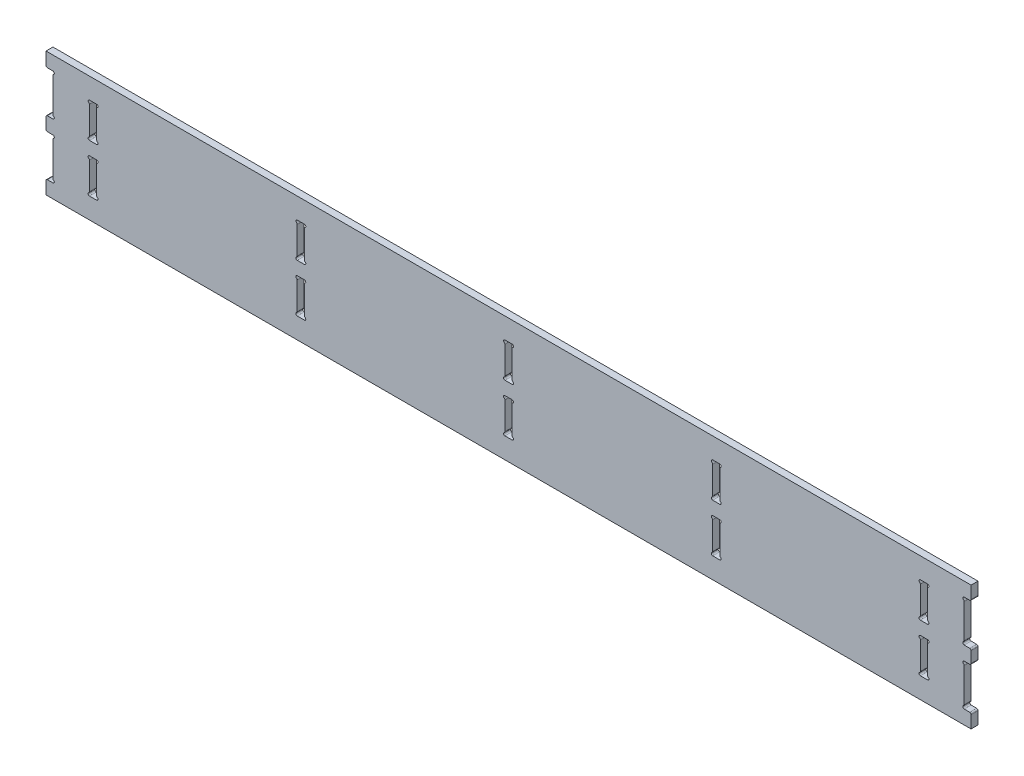
SolidWorks part; units mm, degrees
material "Plain Carbon Steel"
ref_plane "Front Plane" through (0, 0, 0) normal (0, 0, 1) x (1, 0, 0)
ref_plane "Top Plane" through (0, 0, 0) normal (0, 1, 0) x (1, 0, 0)
ref_plane "Right Plane" through (0, 0, 0) normal (1, 0, 0) x (0, 0, -1)
sketch "Sketch2" plane through (0, 0, 0) normal (0, 0, 1) x (1, 0, 0)
  line L0 (55, 0) -> (-55, 0) construction
  line L1 (-334, 90) -> (334, 90)
  line L2 (-334, 90) -> (-334, 0)
  line L3 (-334, 0) -> (334, 0)
  line L4 (334, 90) -> (334, 0)
  point P6 (0, 0)
  dimension "D1" = 668
  dimension "D2" = 90
extrude "Boss-Extrude1" add sketch "Sketch2" along normal blind 5
sketch "Sketch4" plane through (0, 0, 0) normal (0, 0, -1) x (-1, 0, 0)
  line L0 (0, 2.75) -> (0, -2.75) construction
  line L1 (-2.6, 75) -> (2.6, 75)
  line L2 (-2.6, 75) -> (-2.6, 49.8)
  line L3 (-2.6, 49.8) -> (2.6, 49.8)
  line L4 (2.6, 75) -> (2.6, 49.8)
  line L5 (-2.6, 40.2) -> (2.6, 40.2)
  line L6 (-2.6, 40.2) -> (-2.6, 15)
  line L7 (-2.6, 15) -> (2.6, 15)
  line L8 (2.6, 40.2) -> (2.6, 15)
  line L9 (-334, 90) -> (334, 90) construction
  line L10 (2.75, 0) -> (-2.75, 0) construction
  line L11 (147.4, 75) -> (152.6, 75)
  line L12 (147.4, 75) -> (147.4, 49.8)
  line L13 (147.4, 49.8) -> (152.6, 49.8)
  line L14 (152.6, 75) -> (152.6, 49.8)
  line L15 (147.4, 40.2) -> (152.6, 40.2)
  line L16 (147.4, 40.2) -> (147.4, 15)
  line L17 (147.4, 15) -> (152.6, 15)
  line L18 (152.6, 40.2) -> (152.6, 15)
  line L19 (297.4, 75) -> (302.6, 75)
  line L20 (297.4, 75) -> (297.4, 49.8)
  line L21 (297.4, 49.8) -> (302.6, 49.8)
  line L22 (302.6, 75) -> (302.6, 49.8)
  line L23 (297.4, 40.2) -> (302.6, 40.2)
  line L24 (297.4, 40.2) -> (297.4, 15)
  line L25 (297.4, 15) -> (302.6, 15)
  line L26 (302.6, 40.2) -> (302.6, 15)
  line L27 (-302.6, 40.2) -> (-302.6, 15)
  line L28 (-297.4, 15) -> (-302.6, 15)
  line L29 (-297.4, 40.2) -> (-297.4, 15)
  line L30 (-297.4, 40.2) -> (-302.6, 40.2)
  line L31 (-302.6, 75) -> (-302.6, 49.8)
  line L32 (-297.4, 49.8) -> (-302.6, 49.8)
  line L33 (-297.4, 75) -> (-297.4, 49.8)
  line L34 (-297.4, 75) -> (-302.6, 75)
  line L35 (-152.6, 40.2) -> (-152.6, 15)
  line L36 (-147.4, 15) -> (-152.6, 15)
  line L37 (-147.4, 40.2) -> (-147.4, 15)
  line L38 (-147.4, 40.2) -> (-152.6, 40.2)
  line L39 (-152.6, 75) -> (-152.6, 49.8)
  line L40 (-147.4, 49.8) -> (-152.6, 49.8)
  line L41 (-147.4, 75) -> (-147.4, 49.8)
  line L42 (-147.4, 75) -> (-152.6, 75)
  point P8 (0, 75)
  dimension "D1" = 5.2
  dimension "D2" = 15
  dimension "D3" = 25.2
  dimension "D4" = 15
  dimension "D5" = 25.2
  dimension "D6" = 3
extrude "Cut-Extrude2" cut sketch "Sketch4" against normal through all
sketch "Sketch5" plane through (0, 0, 0) normal (0, 0, -1) x (-1, 0, 0)
  line L0 (-302.6, 75) -> (-302.6, 49.8) construction
  line L1 (-297.4, 49.8) -> (-297.4, 75) construction
  line L2 (-302.6, 40.2) -> (-302.6, 15) construction
  line L3 (-297.4, 15) -> (-297.4, 40.2) construction
  line L4 (-297.4, 75) -> (-302.6, 75) construction
  circle A0 centre (-302.6, 74) radius 1
  circle A1 centre (-297.4, 74) radius 1
  circle A2 centre (-302.6, 50.8) radius 1
  circle A3 centre (-297.4, 50.8) radius 1
  circle A4 centre (-302.6, 39.2) radius 1
  circle A5 centre (-297.4, 39.2) radius 1
  circle A6 centre (-302.6, 16) radius 1
  circle A7 centre (-297.4, 16) radius 1
  circle A8 centre (-152.6, 74) radius 1
  circle A9 centre (-147.4, 74) radius 1
  circle A10 centre (-152.6, 50.8) radius 1
  circle A11 centre (-147.4, 50.8) radius 1
  circle A12 centre (-152.6, 39.2) radius 1
  circle A13 centre (-147.4, 39.2) radius 1
  circle A14 centre (-152.6, 16) radius 1
  circle A15 centre (-147.4, 16) radius 1
  circle A16 centre (-2.6, 74) radius 1
  circle A17 centre (2.6, 74) radius 1
  circle A18 centre (-2.6, 50.8) radius 1
  circle A19 centre (2.6, 50.8) radius 1
  circle A20 centre (-2.6, 39.2) radius 1
  circle A21 centre (2.6, 39.2) radius 1
  circle A22 centre (-2.6, 16) radius 1
  circle A23 centre (2.6, 16) radius 1
  circle A24 centre (147.4, 74) radius 1
  circle A25 centre (152.6, 74) radius 1
  circle A26 centre (147.4, 50.8) radius 1
  circle A27 centre (152.6, 50.8) radius 1
  circle A28 centre (147.4, 39.2) radius 1
  circle A29 centre (152.6, 39.2) radius 1
  circle A30 centre (147.4, 16) radius 1
  circle A31 centre (152.6, 16) radius 1
  circle A32 centre (297.4, 74) radius 1
  circle A33 centre (302.6, 74) radius 1
  circle A34 centre (297.4, 50.8) radius 1
  circle A35 centre (302.6, 50.8) radius 1
  circle A36 centre (297.4, 39.2) radius 1
  circle A37 centre (302.6, 39.2) radius 1
  circle A38 centre (297.4, 16) radius 1
  circle A39 centre (302.6, 16) radius 1
  dimension "D1" = 2
  dimension "D2" = 5
extrude "Cut-Extrude3" cut sketch "Sketch5" against normal through all
fillet "Fillet1" radius 1 40 edges at (-302.6, 38.2, 2.5) (-297.4, 38.2, 2.5) (-297.4, 17, 2.5) (-302.6, 17, 2.5) (-302.6, 73, 2.5) (-302.6, 51.8, 2.5) (-297.4, 51.8, 2.5) (-297.4, 73, 2.5) (-152.6, 17, 2.5) (-147.4, 17, 2.5) (-147.4, 38.2, 2.5) (-152.6, 38.2, 2.5) (-152.6, 51.8, 2.5) (-147.4, 51.8, 2.5) (-147.4, 73, 2.5) (-152.6, 73, 2.5) (-2.6, 17, 2.5) (2.6, 17, 2.5) (2.6, 38.2, 2.5) (-2.6, 38.2, 2.5) (-2.6, 51.8, 2.5) (2.6, 51.8, 2.5) (2.6, 73, 2.5) (-2.6, 73, 2.5) (147.4, 17, 2.5) (152.6, 17, 2.5) (152.6, 38.2, 2.5) (147.4, 38.2, 2.5) (147.4, 51.8, 2.5) (152.6, 51.8, 2.5) (152.6, 73, 2.5) (147.4, 73, 2.5) (297.4, 17, 2.5) (302.6, 17, 2.5) (302.6, 38.2, 2.5) (297.4, 38.2, 2.5) (297.4, 51.8, 2.5) (302.6, 51.8, 2.5) (302.6, 73, 2.5) (297.4, 73, 2.5)
sketch "Sketch6" plane through (334, 0, 0) normal (1, 0, 0) x (0, 0, -1)
  line L0 (-5, 0) -> (-5, 90) construction
  line L1 (-5, 80) -> (0, 80)
  line L2 (-5, 80) -> (-5, 50)
  line L3 (-5, 50) -> (0, 50)
  line L4 (0, 80) -> (0, 50)
  line L5 (0, 0) -> (0, 90) construction
  line L6 (-5, 0) -> (0, 0) construction
  line L7 (0, 10) -> (-5, 10)
  line L8 (0, 10) -> (0, 40)
  line L9 (0, 40) -> (-5, 40)
  line L10 (-5, 10) -> (-5, 40)
  line L11 (-5, 90) -> (0, 90) construction
  point P14 (-2.5, 50)
  point P17 (-2.5, 90)
  dimension "D1" = 10
  dimension "D2" = 30
  dimension "D3" = 30
  dimension "D4" = 10
extrude "Cut-Extrude4" cut sketch "Sketch6" against normal blind 5
mirror "Mirror1" about plane through (0, 0, 0) normal (1, 0, 0) of "Cut-Extrude4"
sketch "Sketch7" plane through (0, 0, 0) normal (0, 0, -1) x (-1, 0, 0)
  line L0 (-329, 50) -> (-329, 80) construction
  line L1 (-329, 10) -> (-329, 40) construction
  line L2 (0, 2.75) -> (0, -2.75) construction
  circle A0 centre (-329, 79) radius 1
  circle A1 centre (-329, 51) radius 1
  circle A2 centre (-329, 39) radius 1
  circle A3 centre (-329, 11) radius 1
  circle A4 centre (329, 11) radius 1
  circle A5 centre (329, 39) radius 1
  circle A6 centre (329, 51) radius 1
  circle A7 centre (329, 79) radius 1
  dimension "D1" = 2
extrude "Cut-Extrude5" cut sketch "Sketch7" against normal through all
fillet "Fillet2" radius 1 16 edges at (-334, 10, 2.5) (-329, 12, 2.5) (-329, 38, 2.5) (-334, 40, 2.5) (-334, 50, 2.5) (-329, 52, 2.5) (-329, 78, 2.5) (-334, 80, 2.5) (334, 10, 2.5) (329, 12, 2.5) (329, 38, 2.5) (334, 40, 2.5) (334, 50, 2.5) (329, 52, 2.5) (329, 78, 2.5) (334, 80, 2.5)
